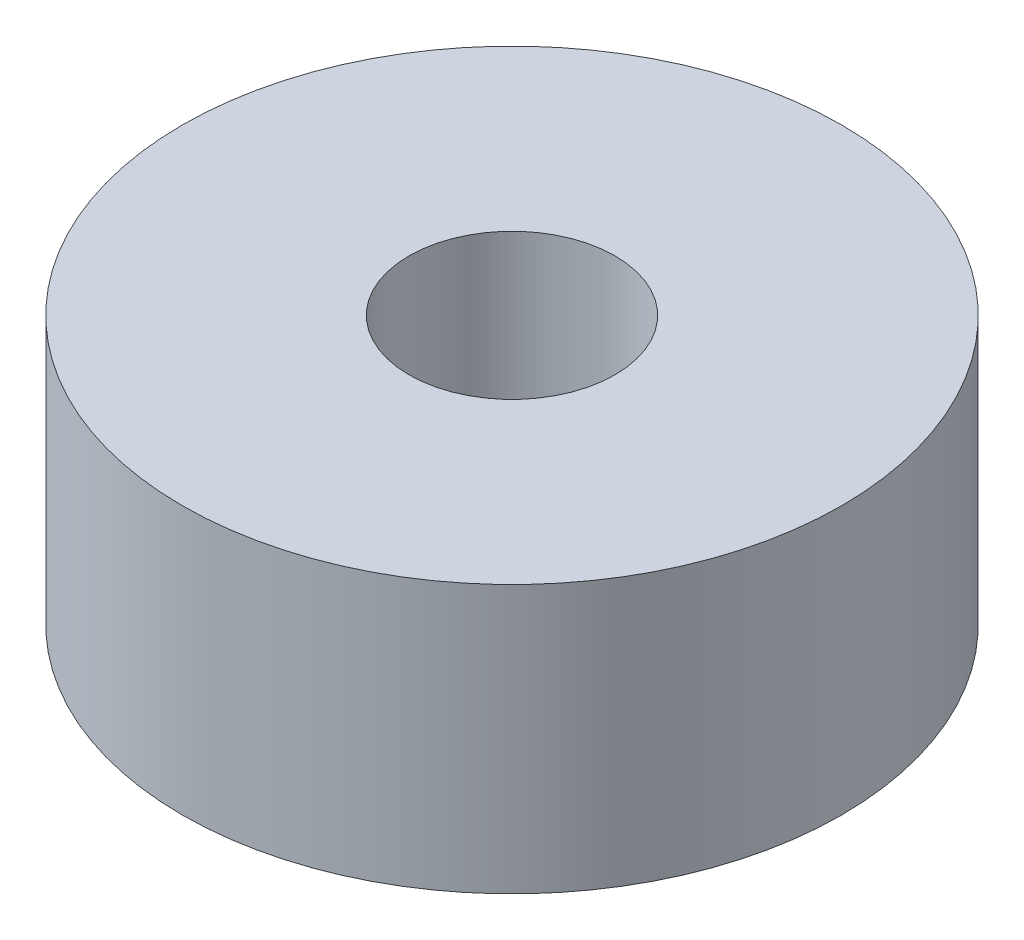
SolidWorks part; units mm, degrees
ref_plane "Front" through (0, 0, 0) normal (0, 0, 1) x (1, 0, 0)
ref_plane "Top" through (0, 0, 0) normal (0, 1, 0) x (1, 0, 0)
ref_plane "Right" through (0, 0, 0) normal (1, 0, 0) x (0, 0, -1)
sketch "Эскиз1" plane through (0, 0, 0) normal (0, 1, 0) x (1, 0, 0)
  circle A0 centre (0, 0) radius 2.5
  circle A1 centre (0, 0) radius 8
extrude "Бобышка-Вытянуть1" add sketch "Эскиз1" along normal blind 6.5
